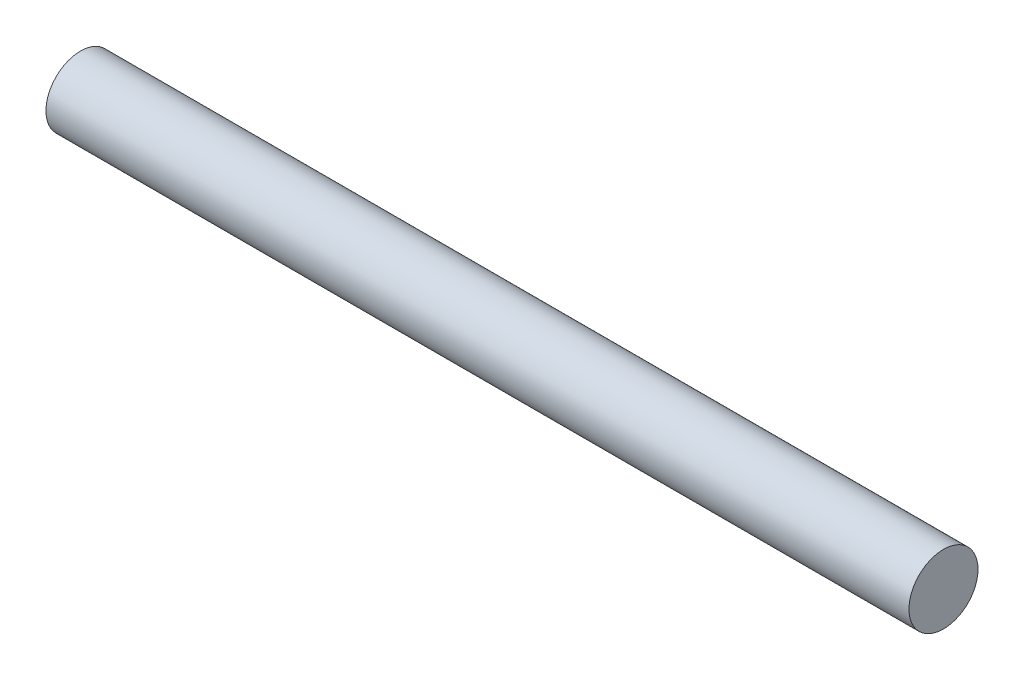
SolidWorks part; units mm, degrees
ref_plane "Alzado" through (0, 0, 0) normal (0, 0, 1) x (1, 0, 0)
ref_plane "Planta" through (0, 0, 0) normal (0, 1, 0) x (1, 0, 0)
ref_plane "Vista lateral" through (0, 0, 0) normal (1, 0, 0) x (0, 0, -1)
sketch "Croquis1" plane through (0, 0, 0) normal (1, 0, 0) x (0, 0, -1)
  circle A0 centre (0, 0) radius 4
  dimension "D1" = 8
extrude "Saliente-Extruir1" add sketch "Croquis1" along normal blind 100
